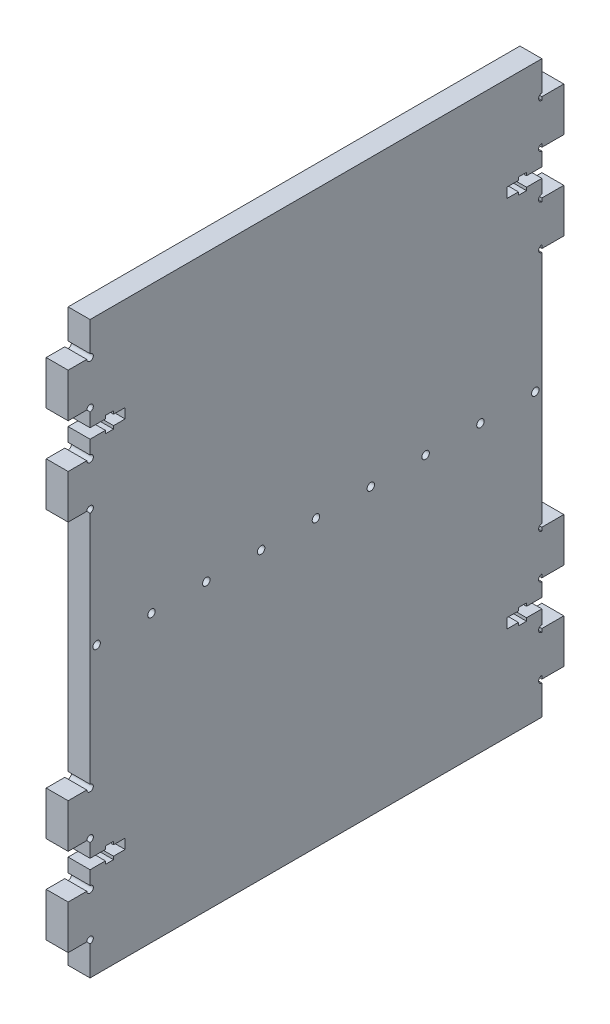
SolidWorks part; units mm, degrees
material "POLICARB. TRANSP."
ref_plane "Front Plane" through (0, 0, 0) normal (0, 0, 1) x (1, 0, 0)
ref_plane "Top Plane" through (0, 0, 0) normal (0, 1, 0) x (1, 0, 0)
ref_plane "Right Plane" through (0, 0, 0) normal (1, 0, 0) x (0, 0, -1)
sketch "Sketch1" plane through (0, 0, 0) normal (1, 0, 0) x (0, 0, -1)
  line L1 (103, 130) -> (-103, 130)
  line L2 (103, 130) -> (103, -130)
  line L3 (103, -130) -> (-103, -130)
  line L4 (-103, 130) -> (-103, -130)
  line L5 (0, -130) -> (0, 130) construction
  line L6 (103, 0) -> (-103, 0) construction
  point P0 (0, 0)
  dimension "D1" = 206
  dimension "D2" = 260
extrude "Extrude1" add sketch "Sketch1" along normal blind 10
sketch "Sketch3" plane through (10, 0, 0) normal (1, 0, 0) x (0, 0, -1)
  line L0 (0, 0) -> (-103, 0) construction
  line L1 (-103, 130) -> (-103, -130) construction
  line L2 (-103, -130) -> (103, -130) construction
  line L3 (-103, -95) -> (-113, -95)
  line L4 (-103, -95) -> (-103, -115)
  line L5 (-103, -115) -> (-113, -115)
  line L6 (-113, -95) -> (-113, -115)
  line L8 (-103, -75) -> (-113, -75)
  line L9 (-103, -75) -> (-103, -55)
  line L10 (-103, -55) -> (-113, -55)
  line L11 (-113, -75) -> (-113, -55)
  dimension "D1" = 15
  dimension "D2" = 20
  dimension "D3" = 10
  dimension "D4" = 20
extrude "Extrude2" add sketch "Sketch3" against normal blind 10
pattern_linear "LPattern1" count 2 spacing 196 count 2 spacing 170 along (0, 1, 0) of "Extrude2"
sketch "Sketch4" plane through (10, 0, 0) normal (1, 0, 0) x (0, 0, -1)
  line L1 (-113, 75) -> (-103, 75)
  line L2 (-113, 75) -> (-113, 55)
  line L3 (-113, 55) -> (-103, 55)
  line L4 (-103, 75) -> (-103, 55)
extrude "Extrude3" [suppressed] cut sketch "Sketch4" against normal blind 10
sketch "Sketch5" plane through (10, 0, 0) normal (1, 0, 0) x (0, 0, -1)
  line L0 (-103, -87.25) -> (-96, -87.25)
  line L1 (-103, -75) -> (-103, -95) construction
  line L2 (-96, -87.25) -> (-96, -88.625)
  line L3 (-96, -88.625) -> (-92.3, -88.625)
  line L4 (-92.3, -88.625) -> (-92.3, -87.25)
  line L5 (-92.3, -87.25) -> (-87, -87.25)
  line L6 (-87, -87.25) -> (-87, -82.75)
  line L7 (-87, -82.75) -> (-92.3, -82.75)
  line L8 (-92.3, -82.75) -> (-92.3, -81.375)
  line L9 (-92.3, -81.375) -> (-96, -81.375)
  line L10 (-96, -81.375) -> (-96, -82.75)
  line L11 (-96, -82.75) -> (-103, -82.75)
  line L12 (-113, -75) -> (-113, -95) construction
  line L13 (-113, -75) -> (-103, -75) construction
  line L14 (-113, -85) -> (-103, -85) construction
  line L15 (-103, -82.75) -> (-103, -87.25)
  dimension "D1" = 4.5
  dimension "D2" = 3.7
  dimension "D3" = 7.25
  dimension "D4" = 7
  dimension "D5" = 16
extrude "Extrude4" cut sketch "Sketch5" against normal blind 10
ref_plane "Plane1" through (0, 0, 0) normal (0, 0, -1) x (-1, 0, 0)
mirror "Mirror1" about plane through (0, 0, 0) normal (0, 0, -1) of "Extrude4"
pattern_linear "LPattern2" count 2 spacing 170 along (0, 1, 0) of "Extrude4", "Mirror1"
sketch "Sketch6" plane through (10, 0, 0) normal (1, 0, 0) x (0, 0, -1)
  line L0 (-104.5, -115) -> (-103, -115)
  line L1 (-103, -115) -> (-103, -116.5)
  line L2 (-104.5, -55) -> (-103, -55)
  line L3 (-104.5, -95) -> (-103, -95)
  line L4 (-103, -95) -> (-103, -93.5)
  line L5 (-103, -55) -> (-103, -53.5)
  line L6 (-104.5, -75) -> (-103, -75)
  line L7 (-103, -75) -> (-103, -76.5)
  arc A0 (-104.5, -55) -> (-103, -53.5) centre (-103, -55) ccw
  arc A1 (-103, -76.5) -> (-104.5, -75) centre (-103, -75) ccw
  arc A2 (-104.5, -95) -> (-103, -93.5) centre (-103, -95) ccw
  arc A3 (-103, -116.5) -> (-104.5, -115) centre (-103, -115) ccw
  dimension "D1" = 3
extrude "Extrude5" cut sketch "Sketch6" against normal blind 10
mirror "Mirror2" about plane through (0, 0, 0) normal (0, 0, -1) of "Extrude5"
ref_plane "Plane2" through (0, 0, 0) normal (0, 1, 0) x (1, 0, 0)
mirror "Mirror3" about plane through (0, 0, 0) normal (0, 1, 0) of "Mirror2", "Extrude5"
hole_wizard "M3 Clearance Hole1" positions "Sketch7" profile "Sketch8" hole size "M3" standard "DIN"
sketch "Sketch7" plane through (10, -130, 293) normal (1, 0, 0) x (0, -1, 0)
  line L0 (-130, 396) -> (-130, 190) construction
  line L1 (-76.5, 396) -> (-183.5, 396) construction
  line L2 (-183.5, 190) -> (-76.5, 190) construction
  point P0 (-130, 368)
  point P3 (-130, 343)
  point P6 (-130, 318)
  point P9 (-130, 293)
  point P12 (-130, 268)
  point P15 (-130, 243)
  point P18 (-130, 218)
  point P36 (-130, 193)
  point P39 (-130, 393)
  dimension "D1" = 25
  dimension "D2" = 25
  dimension "D3" = 25
  dimension "D4" = 25
  dimension "D5" = 25
  dimension "D6" = 25
  dimension "D7" = 28
  dimension "D8" = 25
  dimension "D9" = 25
sketch "Sketch8" plane through (10, 0, -75) normal (0, 1, 0) x (0, 0, -1)
  line L0 (0, 0) -> (0, 11.0215)
  line L1 (0, 11.0215) -> (1.7, 10)
  line L2 (1.7, 10) -> (1.7, 0)
  line L3 (1.7, 0) -> (0, 0)
  line L4 (0, 11.0215) -> (-1.7, 10) construction
  line L5 (0, -6.35) -> (0, 107.95) construction
  dimension "Hole Dia." = 3.4
  dimension "Hole Depth" = 10
  dimension "Drill Angle" = 118
mirror "Mirror4" about plane through (0, 0, 0) normal (0, 0, -1) of "LPattern1", "Extrude2"
